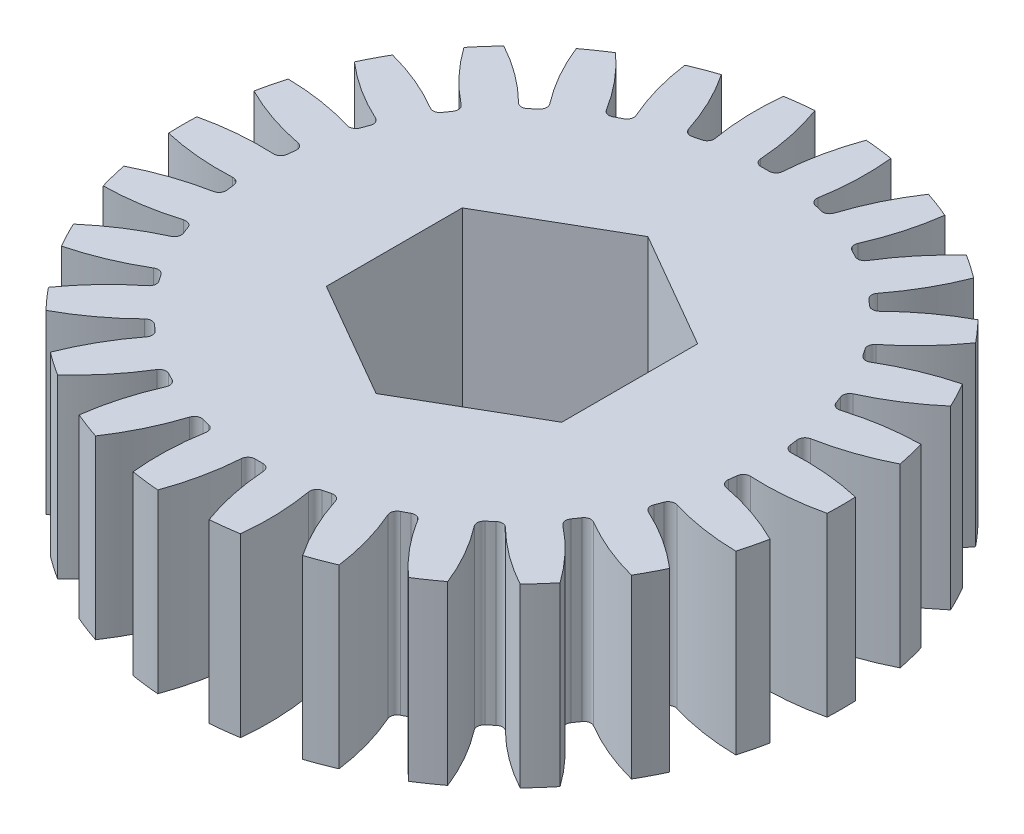
SolidWorks part; units mm, degrees
ref_plane "Front Plane" through (0, 0, 0) normal (0, 0, 1) x (1, 0, 0)
ref_plane "Top Plane" through (0, 0, 0) normal (0, 1, 0) x (1, 0, 0)
ref_plane "Right Plane" through (0, 0, 0) normal (1, 0, 0) x (0, 0, -1)
sketch "Sketch1" plane through (0, 0, 0) normal (0, 1, 0) x (1, 0, 0)
  circle A0 centre (0, 0) radius 16.51
  circle A1 centre (0, 0) radius 17.78
  circle A2 centre (0, 0) radius 13.6525
  dimension "D1" = 33.02
  dimension "D2" = 35.56
  dimension "D3" = 2.8575
extrude "Boss-Extrude1" add sketch "Sketch1" along normal mid plane 9.525 contours A1
sketch "Sketch2" plane through (0, 4.7625, 0) normal (0, 1, 0) x (1, 0, 0)
  line L0 (0, 0) -> (0, -50000) construction
  line L1 (0, 0) -> (50000, 0) construction
  line L2 (-0.9968, 16.4799) -> (0.9968, 16.4799) construction
  line L3 (0, 0) -> (-0.5747, 13.6404) construction
  line L4 (0, 12.6253) -> (-1.6432, 18.979) construction
  line L5 (0, 0) -> (2.1431, 17.6504) construction
  line L6 (0.9968, 16.4799) -> (2.976, 16.2396) construction
  arc A0 (-1.8999, 18.955) -> (-0.5747, 13.6404) centre (-14.1953, 13.0665) cw
  circle A1 centre (0, 0) radius 13.6525 construction
  arc A2 (-13.6525, 0) -> (13.6525, 0) centre (0, 0) ccw
  arc A3 (1.8999, 18.955) -> (0.5747, 13.6404) centre (14.1953, 13.0665) ccw
  arc A4 (0.5747, 13.6404) -> (-0.5747, 13.6404) centre (0, 0) ccw
  arc A6 (1.8999, 18.955) -> (-1.8999, 18.955) centre (0, 0) ccw
  circle A7 centre (0, 0) radius 19.05
  arc A8 (-19.05, 0) -> (19.05, 0) centre (0, 0) ccw
  circle A10 centre (0, 0) radius 16.51 construction
  circle A11 centre (0, 0) radius 17.78 construction
  circle M13 centre (0, 0) radius 17.78
  dimension "D2" = 14.5
  dimension "D3" = 6.923
  dimension "D1" = 1.27
extrude "Cut-Extrude1" cut sketch "Sketch2" against normal blind 9.525 contours A4 A3 A0 M13 | A3 A6 A0 M13
fillet "Fillet1" radius 0.381 2 edges at (0.5747, 0, -13.6404) (-0.5747, 0, -13.6404)
pattern_circular "CirPattern1" count 26 over 360 about axis through (0, 0, 0) along (0, 1, 0) of "Fillet1", "Cut-Extrude1"
sketch "Sketch4" plane through (0, 4.7625, 0) normal (0, 1, 0) x (1, 0, 0)
  line L1 (0, 7.3323) -> (-6.35, 3.6662)
  line L2 (-6.35, 3.6662) -> (-6.35, -3.6662)
  line L3 (-6.35, -3.6662) -> (0, -7.3323)
  line L4 (0, -7.3323) -> (6.35, -3.6662)
  line L5 (6.35, -3.6662) -> (6.35, 3.6662)
  line L6 (6.35, 3.6662) -> (0, 7.3323)
  circle A0 centre (0, 0) radius 6.35 construction
  dimension "D1" = 12.7
extrude "Cut-Extrude2" cut sketch "Sketch4" against normal through all
equation "\"DP\"= 20"
equation "\"Num Teeth\"= 26"
equation "\"D1@Sketch1\"=\"Num Teeth\" / \"DP\""
equation "\"Module\"= 0.05"
equation "\"D2@Sketch1\"=(\"Num Teeth\" +2) * \"Module\""
equation "\"D3@Sketch1\"= \"Module\" * 2.25"
equation "\"D3@Sketch2\"= 180 / \"Num Teeth\""
equation "\"D1@Fillet1\"= .3 * \"Module\""
equation "\"D1@CirPattern1\"= \"Num Teeth\""
